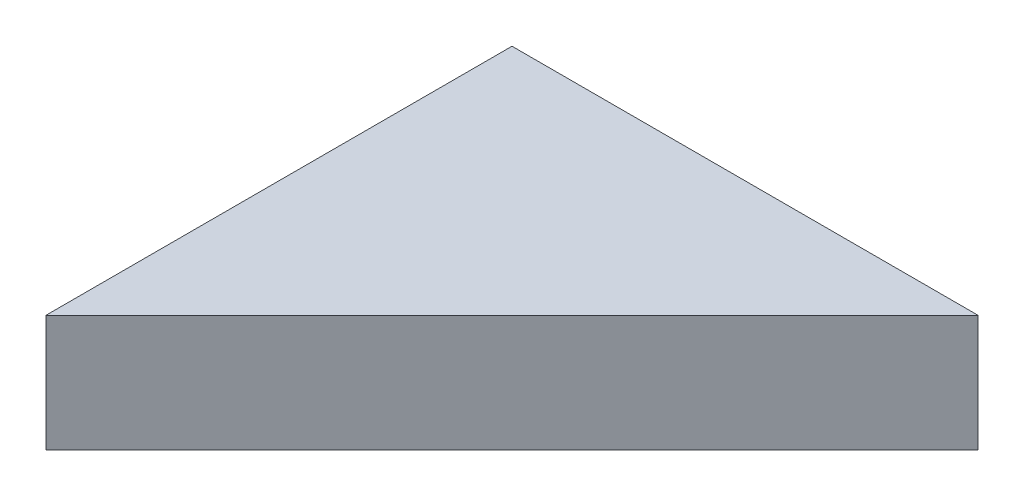
SolidWorks part; units mm, degrees
ref_plane "Front Plane" through (0, 0, 0) normal (0, 0, 1) x (1, 0, 0)
ref_plane "Top Plane" through (0, 0, 0) normal (0, 1, 0) x (1, 0, 0)
ref_plane "Right Plane" through (0, 0, 0) normal (1, 0, 0) x (0, 0, -1)
sketch "Sketch1" plane through (0, 0, 0) normal (0, 1, 0) x (1, 0, 0)
  line L0 (0, 0) -> (0, 60)
  line L1 (0, 60) -> (60, 60)
  line L2 (60, 60) -> (0, 0)
extrude "Boss-Extrude1" add sketch "Sketch1" along normal blind 15 contours L2 L0 L1
